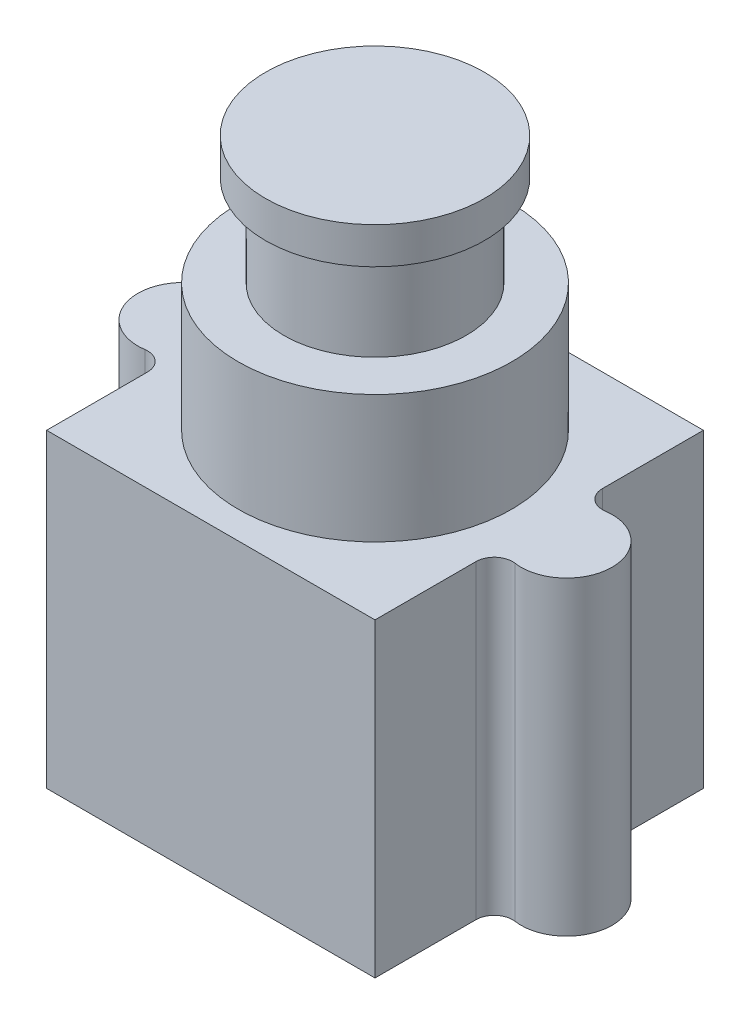
SolidWorks part; units mm, degrees
ref_plane "Front Plane" through (0, 0, 0) normal (0, 0, 1) x (1, 0, 0)
ref_plane "Top Plane" through (0, 0, 0) normal (0, 1, 0) x (1, 0, 0)
ref_plane "Right Plane" through (0, 0, 0) normal (1, 0, 0) x (0, 0, -1)
sketch "Sketch1" plane through (0, 0, 0) normal (0, 1, 0) x (1, 0, 0)
  line L1 (9, 9) -> (-9, 9)
  line L2 (9, 9) -> (9, -9)
  line L3 (9, -9) -> (-9, -9)
  line L4 (-9, 9) -> (-9, -9)
  line L5 (9, 9) -> (-9, -9) construction
  line L6 (9, -9) -> (-9, 9) construction
  point P0 (0, 0)
  dimension "D1" = 18
  dimension "D2" = 18
extrude "Boss-Extrude1" add sketch "Sketch1" along normal blind 17
sketch "Sketch2" plane through (0, 17, 0) normal (0, 1, 0) x (1, 0, 0)
  circle A0 centre (0, 0) radius 7.5
  dimension "D1" = 15
extrude "Boss-Extrude2" add sketch "Sketch2" along normal blind 7
sketch "Sketch3" plane through (0, 24, 0) normal (0, 1, 0) x (1, 0, 0)
  circle A0 centre (0, 0) radius 5
  dimension "D1" = 10
extrude "Boss-Extrude3" add sketch "Sketch3" along normal blind 5
sketch "Sketch4" plane through (0, 29, 0) normal (0, 1, 0) x (1, 0, 0)
  circle A0 centre (0, 0) radius 6
  dimension "D1" = 12
extrude "Boss-Extrude4" add sketch "Sketch4" along normal blind 2
sketch "Sketch5" plane through (0, 0, 0) normal (0, -1, 0) x (1, 0, 0)
  line L0 (0, 0) -> (0, -50000) construction
  circle A0 centre (-10.5, 0) radius 2.5
  circle A1 centre (10.5, 0) radius 2.5
  dimension "D1" = 5
  dimension "D2" = 21
extrude "Boss-Extrude5" add sketch "Sketch5" against normal up to surface (17 mm away) up to face at (0, 17, -7.5)
fillet "Fillet1" radius 1 4 edges at (9, 8.5, -2) (9, 8.5, 2) (-9, 8.5, 2) (-9, 8.5, -2)
sketch "Sketch6" plane through (0, 0, 0) normal (0, -1, 0) x (1, 0, 0)
  circle A0 centre (-10.5, 0) radius 1.25
  circle A1 centre (10.5, 0) radius 1.25
  dimension "D1" = 2.5
extrude "Cut-Extrude1" cut sketch "Sketch6" against normal blind 6
